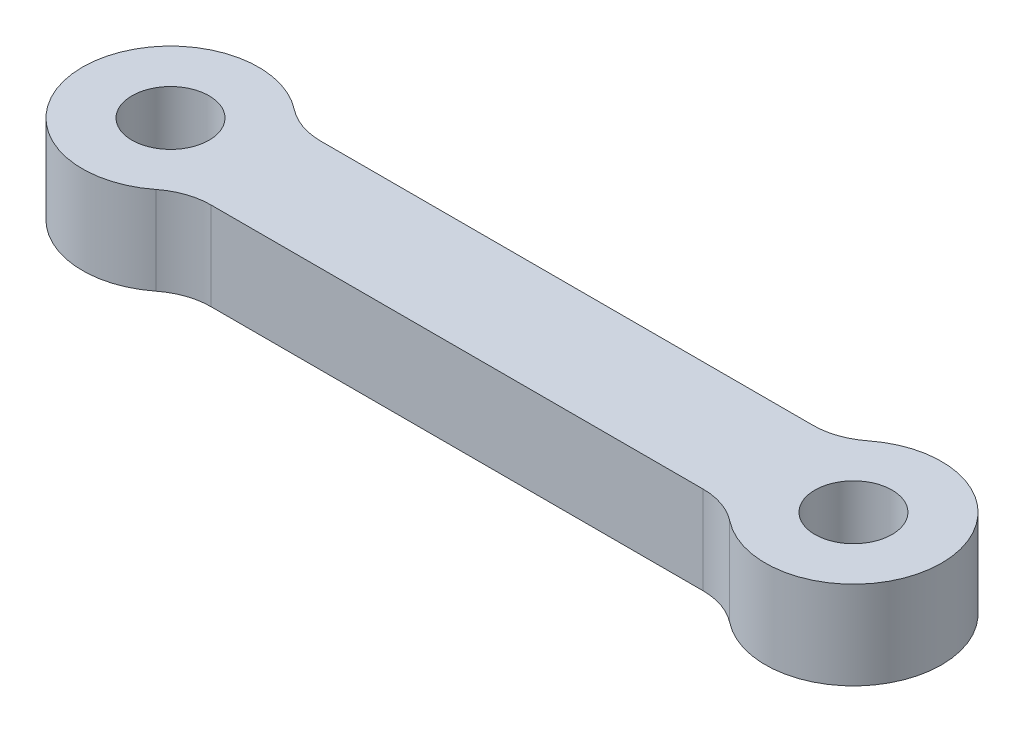
SolidWorks part; units mm, degrees
ref_plane "Front Plane" through (0, 0, 0) normal (0, 0, 1) x (1, 0, 0)
ref_plane "Top Plane" through (0, 0, 0) normal (0, 1, 0) x (1, 0, 0)
ref_plane "Right Plane" through (0, 0, 0) normal (1, 0, 0) x (0, 0, -1)
sketch "Sketch1" plane through (0, 0, 0) normal (0, 1, 0) x (1, 0, 0)
  line L0 (3.1225, 2.5) -> (27.8775, 2.5)
  line L1 (4, 0) -> (27, 0) construction
  line L2 (3.1225, -2.5) -> (27.8775, -2.5)
  circle A0 centre (0, 0) radius 1.75
  circle A1 centre (0, 0) radius 4
  circle A2 centre (31, 0) radius 1.75
  circle A3 centre (31, 0) radius 4
  dimension "D1" = 3.5
  dimension "D2" = 8
  dimension "D3" = 3.5
  dimension "D4" = 8
  dimension "D5" = 31
  dimension "D6" = 5
extrude "Boss-Extrude1" add sketch "Sketch1" along normal blind 4 contours A1 A0 | A1 L1 A3 L0 | L1 A1 L2 A3 | A3 A2
fillet "Fillet1" radius 3 4 edges at (27.8775, 2, 2.5) (3.1225, 2, -2.5) (27.8775, 2, -2.5) (3.1225, 2, 2.5)
